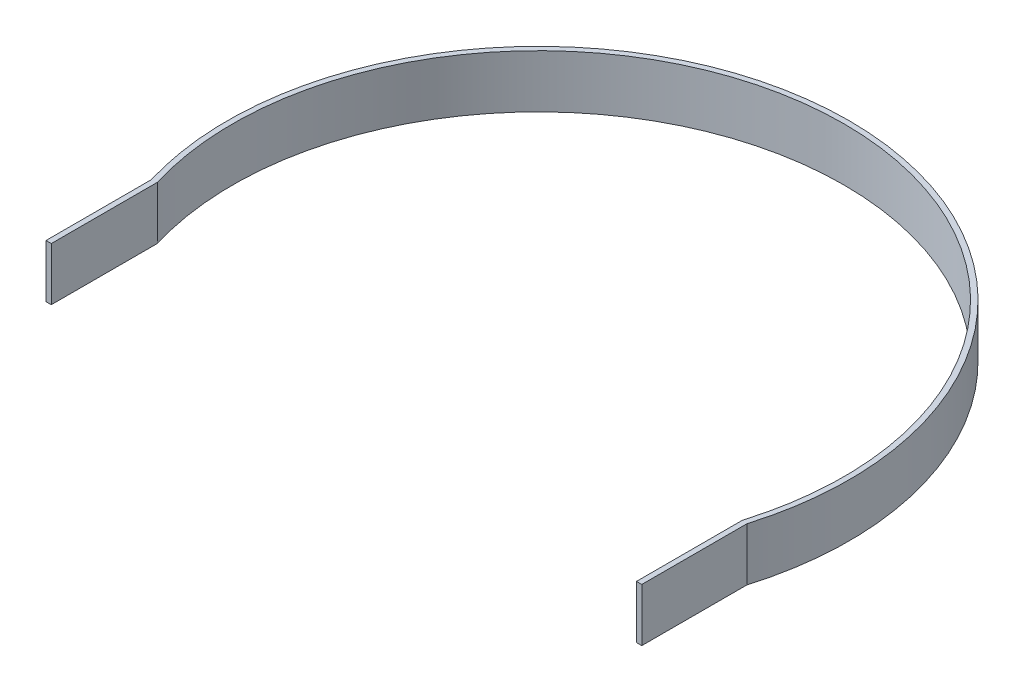
SolidWorks part; units mm, degrees
material "C355.0-T61 Permanent Mold cast (SS)"
ref_plane "Front Plane" through (0, 0, 0) normal (0, 0, 1) x (1, 0, 0)
ref_plane "Top Plane" through (0, 0, 0) normal (0, 1, 0) x (1, 0, 0)
ref_plane "Right Plane" through (0, 0, 0) normal (1, 0, 0) x (0, 0, -1)
sketch "Sketch1" plane through (0, 0, 0) normal (0, 1, 0) x (1, 0, 0)
  line L0 (-55.2, -16.6787) -> (-55.2, -36.6787)
  line L1 (55.2, -16.6787) -> (55.2, -36.6787)
  arc A0 (-55.2, -16.6787) -> (55.2, -16.6787) centre (0, 0) cw
  point P4 (0, 0)
  dimension "D1" = 110.4
  dimension "D3" = 255
  dimension "D2" = 20
extrude "Extrude-Thin1" add sketch "Sketch1" along normal mid plane 10 thin
